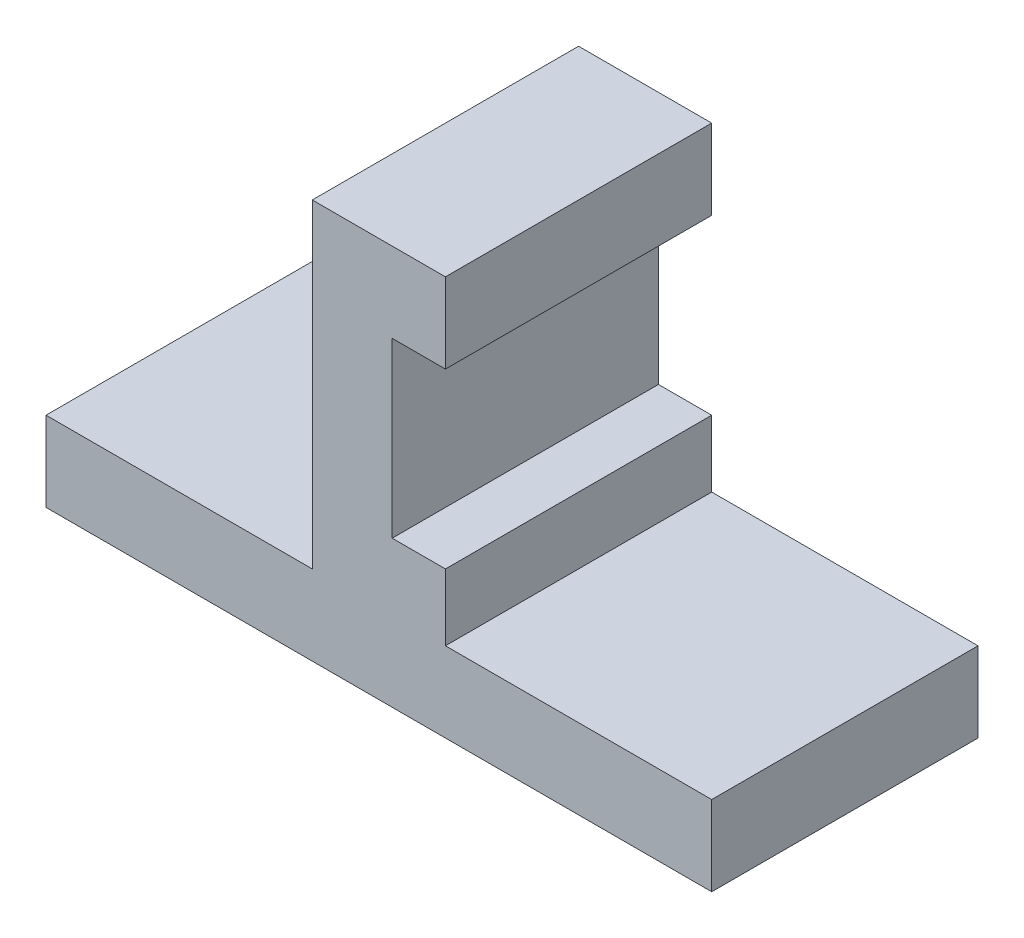
SolidWorks part; units mm, degrees
ref_plane "Front Plane" through (0, 0, 0) normal (0, 0, 1) x (1, 0, 0)
ref_plane "Top Plane" through (0, 0, 0) normal (0, 1, 0) x (1, 0, 0)
ref_plane "Right Plane" through (0, 0, 0) normal (1, 0, 0) x (0, 0, -1)
sketch "Sketch1" plane through (0, 0, 0) normal (0, 1, 0) x (1, 0, 0)
  line L1 (-12.5, 5) -> (12.5, 5)
  line L2 (-12.5, 5) -> (-12.5, -5)
  line L3 (-12.5, -5) -> (12.5, -5)
  line L4 (12.5, 5) -> (12.5, -5)
  line L5 (-12.5, 5) -> (12.5, -5) construction
  line L6 (-12.5, -5) -> (12.5, 5) construction
  point P0 (0, 0)
  dimension "D1" = 25
  dimension "D2" = 10
extrude "Boss-Extrude2" add sketch "Sketch1" along normal blind 3
sketch "Sketch2" plane through (0, 3, 0) normal (0, 1, 0) x (1, 0, 0)
  line L0 (-12.5, -5) -> (12.5, -5) construction
  line L1 (-2.5, 5) -> (2.5, 5)
  line L2 (-2.5, 5) -> (-2.5, -5)
  line L3 (-2.5, -5) -> (2.5, -5)
  line L4 (2.5, 5) -> (2.5, -5)
  line L5 (-2.5, 5) -> (2.5, -5) construction
  line L6 (-2.5, -5) -> (2.5, 5) construction
  point P0 (0, 0)
  dimension "D1" = 5
extrude "Boss-Extrude4" add sketch "Sketch2" along normal blind 12
sketch "Sketch4" plane through (2.5, 0, 0) normal (1, 0, 0) x (0, 0, -1)
  line L0 (5, 15) -> (5, 3) construction
  line L1 (-5, 12) -> (5, 12)
  line L2 (-5, 12) -> (-5, 5.5)
  line L3 (-5, 5.5) -> (5, 5.5)
  line L4 (5, 12) -> (5, 5.5)
  line L5 (-5, 12) -> (5, 5.5) construction
  line L6 (-5, 5.5) -> (5, 12) construction
  line L7 (-5, 15) -> (5, 15) construction
  point P0 (0, 8.75)
  dimension "D1" = 6.5
  dimension "D2" = 3
extrude "Cut-Extrude1" cut sketch "Sketch4" against normal blind 2
